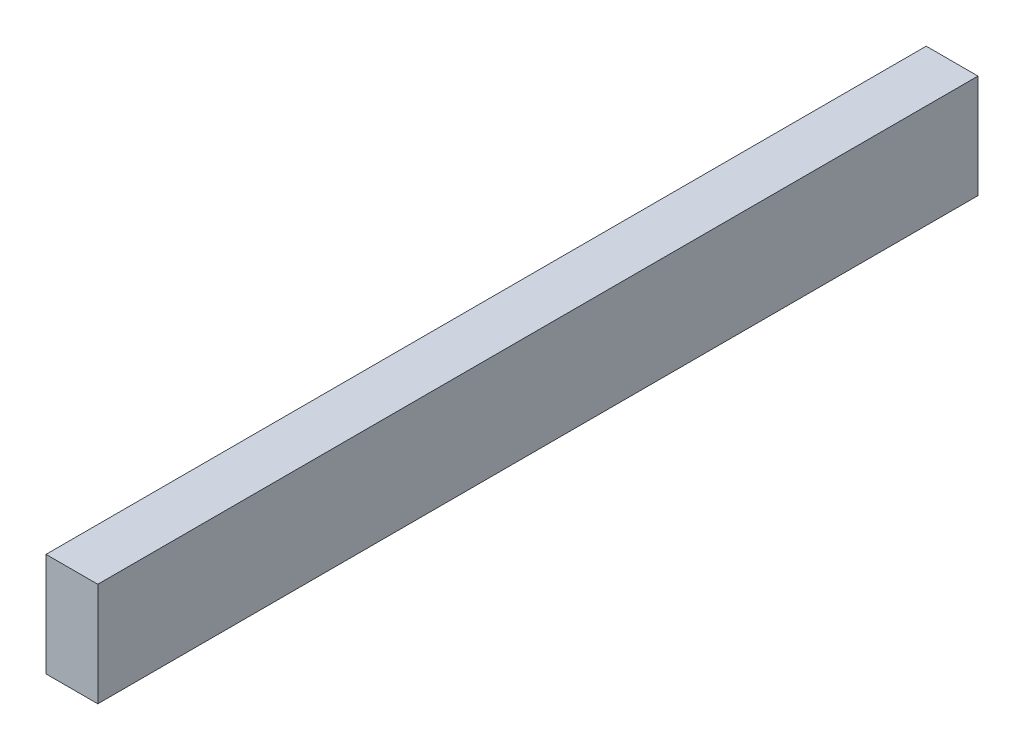
SolidWorks part; units mm, degrees
ref_plane "Front Plane" through (0, 0, 0) normal (0, 0, 1) x (1, 0, 0)
ref_plane "Top Plane" through (0, 0, 0) normal (0, 1, 0) x (1, 0, 0)
ref_plane "Right Plane" through (0, 0, 0) normal (1, 0, 0) x (0, 0, -1)
sketch "Sketch1" plane through (0, 0, 0) normal (0, 0, 1) x (1, 0, 0)
  line L1 (-25.4, -50.8) -> (25.4, -50.8)
  line L2 (-25.4, -50.8) -> (-25.4, 50.8)
  line L3 (-25.4, 50.8) -> (25.4, 50.8)
  line L4 (25.4, -50.8) -> (25.4, 50.8)
  line L5 (-25.4, -50.8) -> (25.4, 50.8) construction
  line L6 (-25.4, 50.8) -> (25.4, -50.8) construction
  point P0 (0, 0)
  dimension "D1" = 50.8
  dimension "D2" = 101.6
extrude "Boss-Extrude1" add sketch "Sketch1" along normal blind 863.6
